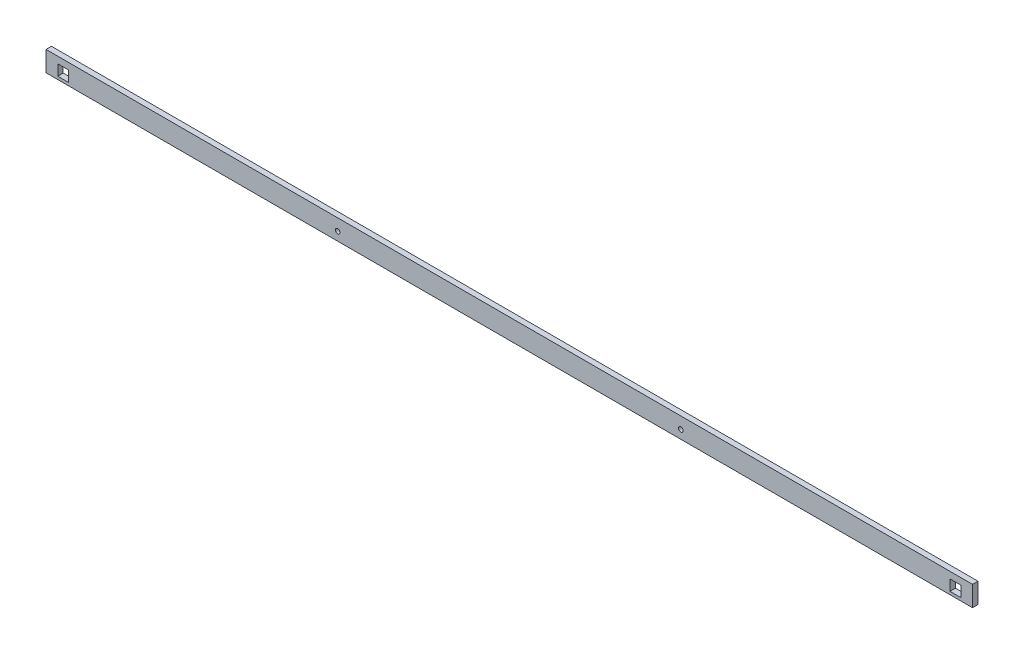
SolidWorks part; units mm, degrees
ref_plane "Front Plane" through (0, 0, 0) normal (0, 0, 1) x (1, 0, 0)
ref_plane "Top Plane" through (0, 0, 0) normal (0, 1, 0) x (1, 0, 0)
ref_plane "Right Plane" through (0, 0, 0) normal (1, 0, 0) x (0, 0, -1)
sketch "Sketch1" plane through (0, 0, 0) normal (0, 0, 1) x (1, 0, 0)
  line L1 (-270, 5.9) -> (270, 5.9)
  line L2 (-270, 5.9) -> (-270, -5.9)
  line L3 (-270, -5.9) -> (270, -5.9)
  line L4 (270, 5.9) -> (270, -5.9)
  line L5 (-270, 5.9) -> (270, -5.9) construction
  line L6 (-270, -5.9) -> (270, 5.9) construction
  point P0 (0, 0)
  dimension "D1" = 11.8
  dimension "D2" = 540
extrude "Boss-Extrude1" add sketch "Sketch1" along normal blind 3.18
sketch "Sketch2" plane through (0, 0, 3.18) normal (0, 0, 1) x (1, 0, 0)
  line L0 (270, -1.05) -> (260, -1.05) construction
  line L2 (270, 5.9) -> (-270, 5.9) construction
  line L4 (256.86, 2.09) -> (263.14, 2.09)
  line L5 (256.86, 2.09) -> (256.86, -4.19)
  line L6 (256.86, -4.19) -> (263.14, -4.19)
  line L7 (263.14, 2.09) -> (263.14, -4.19)
  line L8 (256.86, 2.09) -> (263.14, -4.19) construction
  line L9 (256.86, -4.19) -> (263.14, 2.09) construction
  dimension "D2" = 6.28
  dimension "D1" = 10
  dimension "D3" = 6.95
  dimension "D4" = 6.28
extrude "Cut-Extrude1" cut sketch "Sketch2" against normal up to next
mirror "Mirror1" about plane through (0, 0, 0) normal (1, 0, 0) of "Cut-Extrude1"
sketch "Sketch3" plane through (0, 0, 3.18) normal (0, 0, 1) x (1, 0, 0)
  line L0 (0, -0.9) -> (100, -0.9) construction
  line L1 (-270, -5.9) -> (270, -5.9) construction
  circle A0 centre (100, -0.9) radius 1.35
  dimension "D3" = 2.7
  dimension "D1" = 100
  dimension "D2" = 5
extrude "Cut-Extrude2" cut sketch "Sketch3" against normal up to next
mirror "Mirror2" about plane through (0, 0, 0) normal (1, 0, 0) of "Cut-Extrude2"
